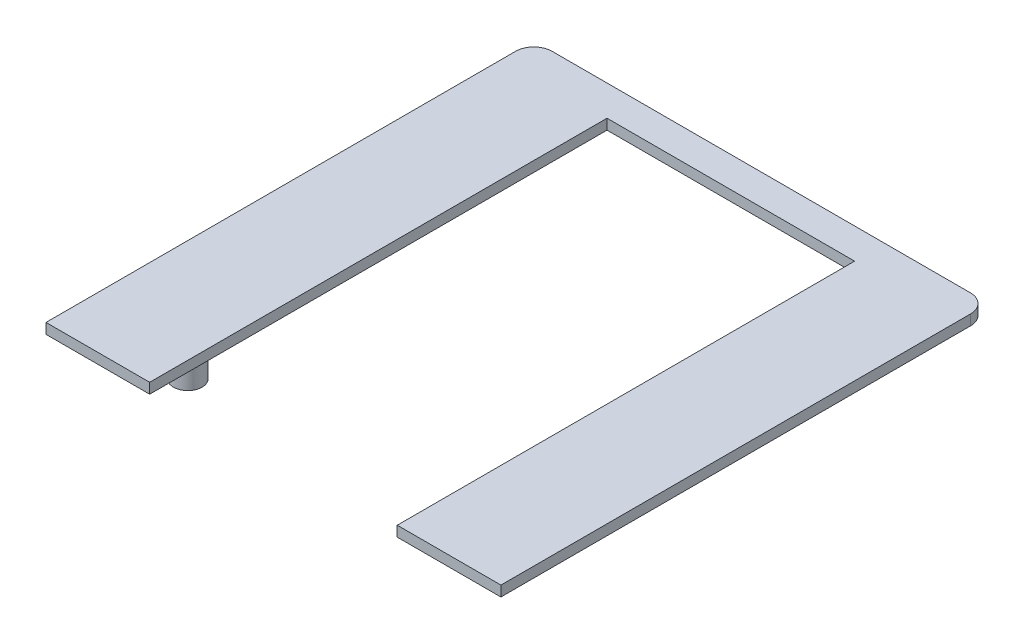
SolidWorks part; units mm, degrees
ref_plane "Front Plane" through (0, 0, 0) normal (0, 0, 1) x (1, 0, 0)
ref_plane "Top Plane" through (0, 0, 0) normal (0, 1, 0) x (1, 0, 0)
ref_plane "Right Plane" through (0, 0, 0) normal (1, 0, 0) x (0, 0, -1)
sketch "Sketch1" plane through (0, 0, 0) normal (0, 1, 0) x (1, 0, 0)
  line L0 (0, 0) -> (0, 80)
  line L1 (0, 80) -> (37.3, 80)
  line L2 (37.3, 80) -> (37.3, 75)
  line L3 (37.3, 75) -> (17, 75)
  line L4 (17, 75) -> (17, 0)
  line L5 (17, 0) -> (0, 0)
  dimension "D1" = 37.3
  dimension "D2" = 20.3
  dimension "D3" = 5
  dimension "D4" = 80
extrude "Boss-Extrude1" add sketch "Sketch1" along normal blind 1.7
sketch "Sketch2" plane through (0, 0, 0) normal (0, -1, 0) x (-1, 0, 0)
  line L0 (-37.3, 80) -> (0, 80) construction
  line L1 (-17, 0) -> (-17, 75) construction
  line L2 (0, 0) -> (-17, 0) construction
  line L3 (0, 80) -> (0, 0) construction
  circle A0 centre (-13.25, 10) radius 2.35
  circle A1 centre (-8, 72) radius 2.35
  dimension "D2" = 8
  dimension "D3" = 3.75
  dimension "D4" = 10
  dimension "D5" = 4.7
  dimension "D1" = 8
extrude "Boss-Extrude2" add sketch "Sketch2" along normal blind 4.7
fillet "Fillet1" radius 3 1 edges at (0, 0.85, -80)
sketch "Sketch3" plane through (0, 0, 0) normal (0, -1, 0) x (-1, 0, 0)
  line L0 (0, 77) -> (0, 0) construction
  line L1 (-37.3, 80) -> (-3, 80) construction
  circle A0 centre (-13.25, 61.25) radius 2.4
  dimension "D1" = 13.25
  dimension "D2" = 18.75
  dimension "D3" = 4.8
extrude "Cut-Extrude1" cut sketch "Sketch3" against normal blind 1
mirror "Mirror3" about plane through (37.3, 1.7, -80) normal (-1, 0, 0) of bodies 104
